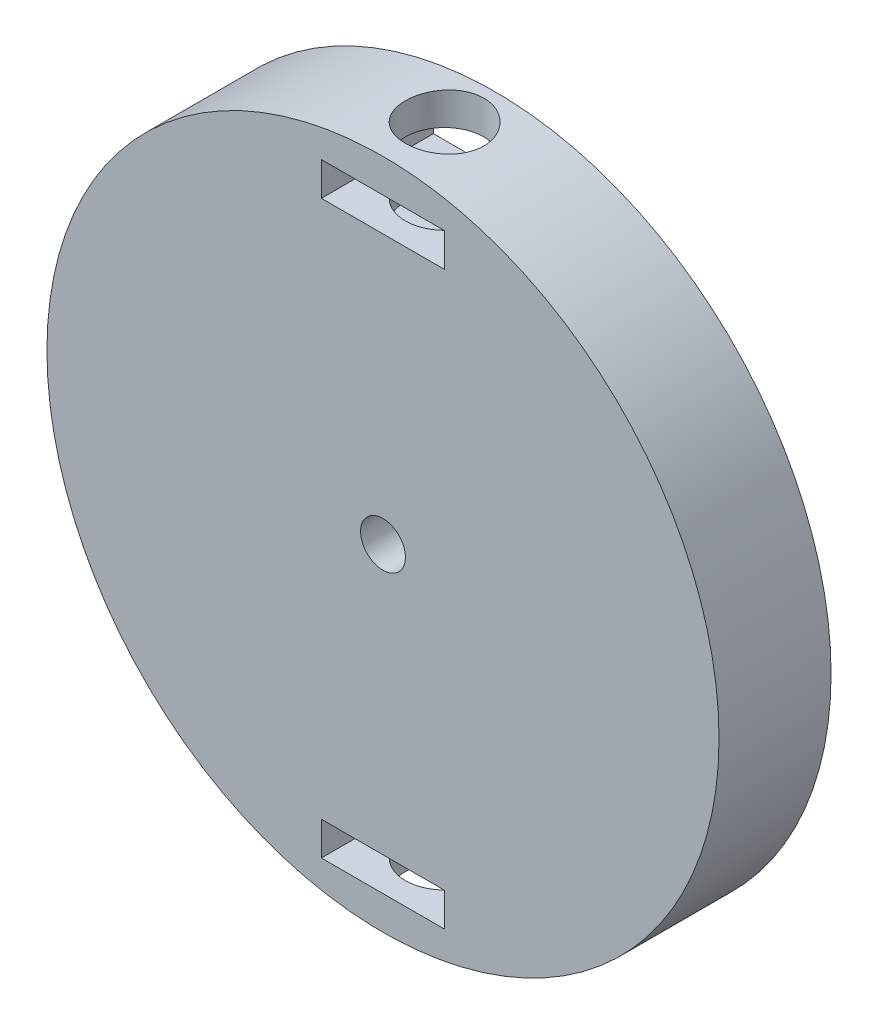
SolidWorks part; units mm, degrees
ref_plane "Front Plane" through (0, 0, 0) normal (0, 0, 1) x (1, 0, 0)
ref_plane "Top Plane" through (0, 0, 0) normal (0, 1, 0) x (1, 0, 0)
ref_plane "Right Plane" through (0, 0, 0) normal (1, 0, 0) x (0, 0, -1)
sketch "Sketch1" plane through (0, 0, 0) normal (0, 0, 1) x (1, 0, 0)
  circle A0 centre (0, 0) radius 30
  dimension "D1" = 60
extrude "Boss-Extrude1" add sketch "Sketch1" along normal blind 10
ref_plane "Plane1" through (0, -30, 0) normal (0, -1, 0) x (-1, 0, 0)
sketch "Sketch10" plane through (0, -30, 0) normal (0, -1, 0) x (-1, 0, 0)
  line L1 (0, -1) -> (1.1394, -1) construction
  line L2 (30, 0) -> (-30, 0) construction
  circle A0 centre (0, -4.5) radius 3.5
  dimension "D1" = 7
  dimension "D2" = 1
  dimension "D3" = 3.5
extrude "Cut-Extrude6" cut sketch "Sketch10" against normal blind 8
mirror "Mirror2" about plane through (0, 0, 0) normal (0, 1, 0) of "Cut-Extrude6"
sketch "Sketch22" plane through (0, 0, 0) normal (0, 0, -1) x (-1, 0, 0)
  line L0 (0, 30) -> (4.4537, 30) construction
  line L1 (4.4537, 30) -> (-5.3728, 30) construction
  circle A0 centre (0, 0) radius 30 construction
sketch "Sketch23" plane through (0, 0, 0) normal (0, 0, -1) x (-1, 0, 0)
  line L0 (0, 30) -> (4.4537, 30) construction
  line L1 (-5.5, 27) -> (5.5, 27)
  line L2 (-5.5, 27) -> (-5.5, 24)
  line L3 (-5.5, 24) -> (5.5, 24)
  line L4 (5.5, 27) -> (5.5, 24)
  line L5 (-5.5, 27) -> (5.5, 24) construction
  line L6 (-5.5, 24) -> (5.5, 27) construction
  point P0 (0, 25.5)
  dimension "D1" = 3
  dimension "D2" = 11
  dimension "D3" = 3
extrude "Cut-Extrude8" cut sketch "Sketch23" against normal blind 10
mirror "Mirror3" about plane through (0, 0, 0) normal (0, 1, 0) of "Cut-Extrude8"
sketch "Sketch24" plane through (0, 0, 0) normal (0, 0, -1) x (-1, 0, 0)
  circle A0 centre (0, 0) radius 2
  dimension "D1" = 4
extrude "Cut-Extrude9" cut sketch "Sketch24" against normal blind 10
